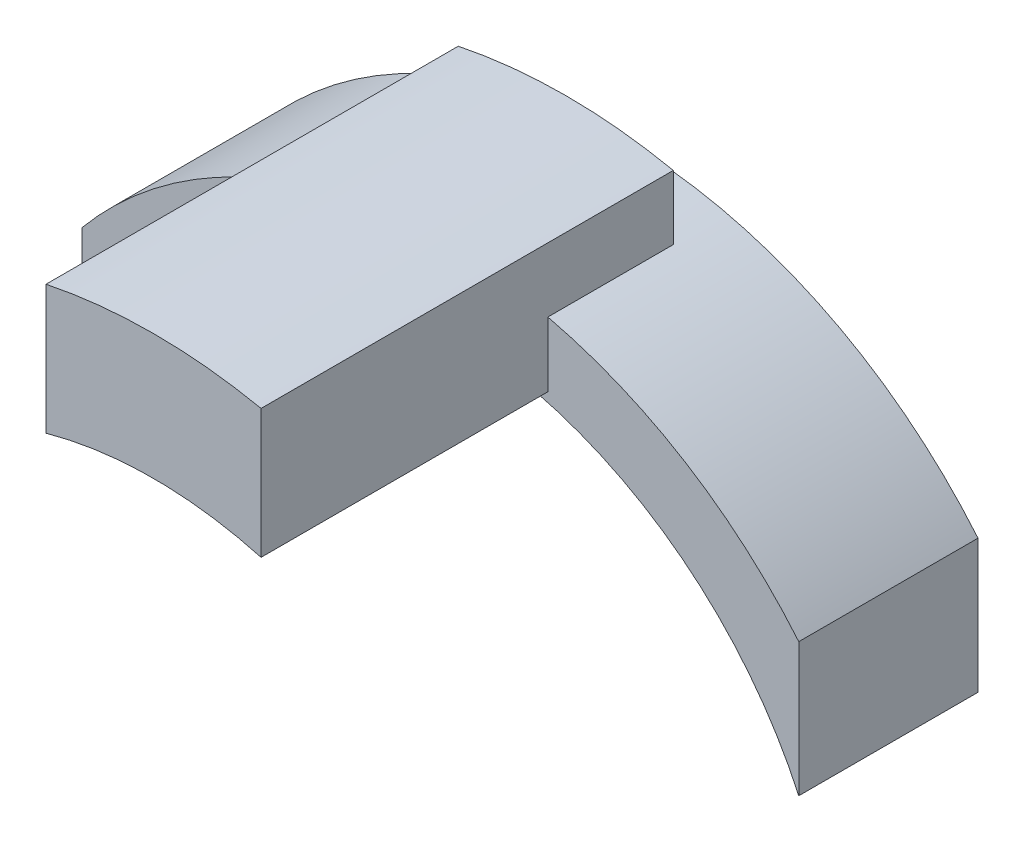
SolidWorks part; units mm, degrees
ref_plane "Front Plane" through (0, 0, 0) normal (0, 0, 1) x (1, 0, 0)
ref_plane "Top Plane" through (0, 0, 0) normal (0, 1, 0) x (1, 0, 0)
ref_plane "Right Plane" through (0, 0, 0) normal (1, 0, 0) x (0, 0, -1)
sketch "Sketch1" plane through (0, 0, 0) normal (0, 0, 1) x (1, 0, 0)
  line L0 (-20, 9.1652) -> (-20, 16.6132)
  line L1 (20, 16.6132) -> (20, 9.1652)
  arc A0 (20, 9.1652) -> (-20, 9.1652) centre (0, 0) ccw
  arc A1 (20, 16.6132) -> (-20, 16.6132) centre (0, 0) ccw
  dimension "D1" = 44
  dimension "D3" = 4
  dimension "D2" = 40
extrude "Extrude1" add sketch "Sketch1" along normal mid plane 10
sketch "Sketch2" plane through (0, 0, 5) normal (0, 0, -1) x (-1, 0, 0)
  line L0 (6, 21.6852) -> (6, 28.8834)
  line L1 (-6, 28.8834) -> (-6, 21.6852)
  arc A0 (6, 28.8834) -> (-6, 28.8834) centre (0, 0) ccw
  arc A2 (6, 21.6852) -> (-6, 21.6852) centre (0, 0) ccw
  arc A3 (20, 9.1652) -> (-20, 9.1652) centre (0, 0) ccw construction
  dimension "D2" = 7
  dimension "D3" = 0.5
  dimension "D1" = 12
extrude "Extrude2" add sketch "Sketch2" against normal blind 16 and the other way blind 7
